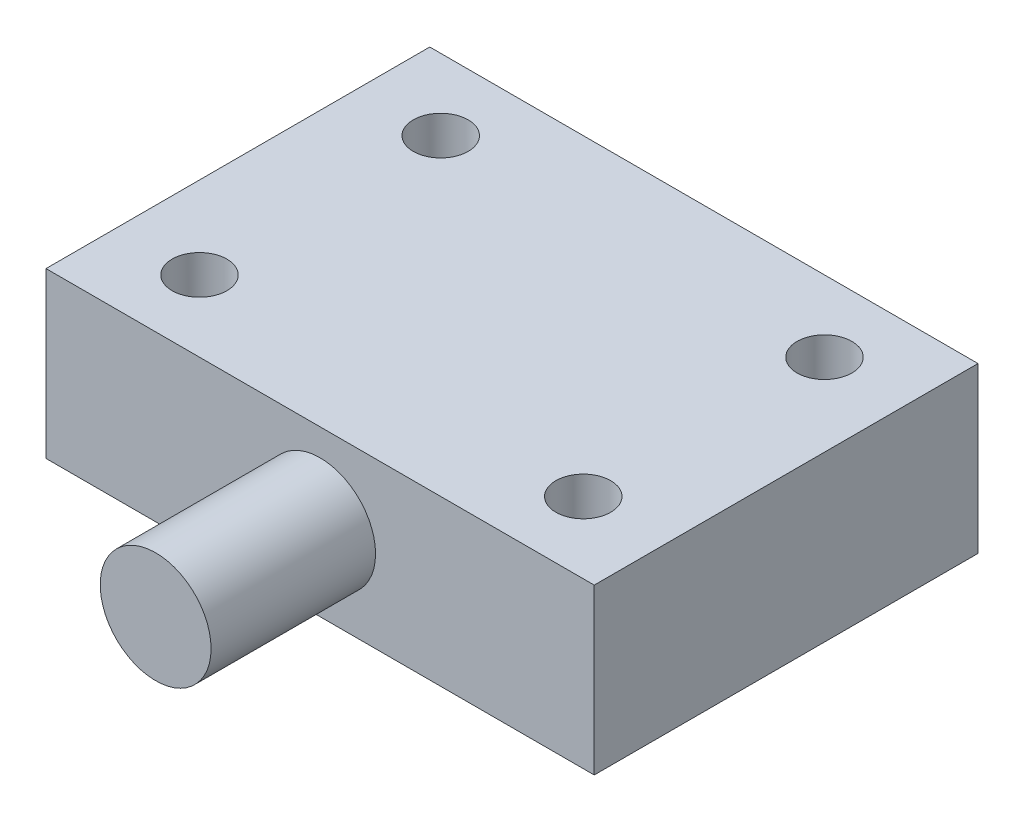
SolidWorks part; units mm, degrees
ref_plane "Front Plane" through (0, 0, 0) normal (0, 0, 1) x (1, 0, 0)
ref_plane "Top Plane" through (0, 0, 0) normal (0, 1, 0) x (1, 0, 0)
ref_plane "Right Plane" through (0, 0, 0) normal (1, 0, 0) x (0, 0, -1)
sketch "Sketch1" plane through (0, 0, 0) normal (0, 0, 1) x (1, 0, 0)
  line L1 (-25, 7.5) -> (25, 7.5)
  line L2 (-25, 7.5) -> (-25, -7.5)
  line L3 (-25, -7.5) -> (25, -7.5)
  line L4 (25, 7.5) -> (25, -7.5)
  line L5 (-25, 7.5) -> (25, -7.5) construction
  line L6 (-25, -7.5) -> (25, 7.5) construction
  point P0 (0, 0)
  dimension "D1" = 15
  dimension "D2" = 50
extrude "Boss-Extrude1" add sketch "Sketch1" along normal blind 35
sketch "Sketch2" plane through (0, 7.5, 0) normal (0, 1, 0) x (1, 0, 0)
  line L1 (25, 0) -> (-25, 0) construction
  line L3 (25, -35) -> (25, 0) construction
  line L4 (25, -35) -> (-25, -35) construction
  line L5 (0, 0) -> (0, -35) construction
  circle A0 centre (17.5, -6.5) radius 2.5
  circle A1 centre (17.5, -28.5) radius 2.5
  circle A2 centre (-17.5, -28.5) radius 2.5
  circle A3 centre (-17.5, -6.5) radius 2.5
  dimension "D1" = 6.5
  dimension "D3" = 22
  dimension "D2" = 7.5
extrude "Cut-Extrude1" cut sketch "Sketch2" against normal blind 30
sketch "Sketch3" plane through (0, 0, 35) normal (0, 0, 1) x (1, 0, 0)
  circle A0 centre (0, 0) radius 5.055
  dimension "D1" = 10.11
extrude "Boss-Extrude2" add sketch "Sketch3" along normal blind 15
